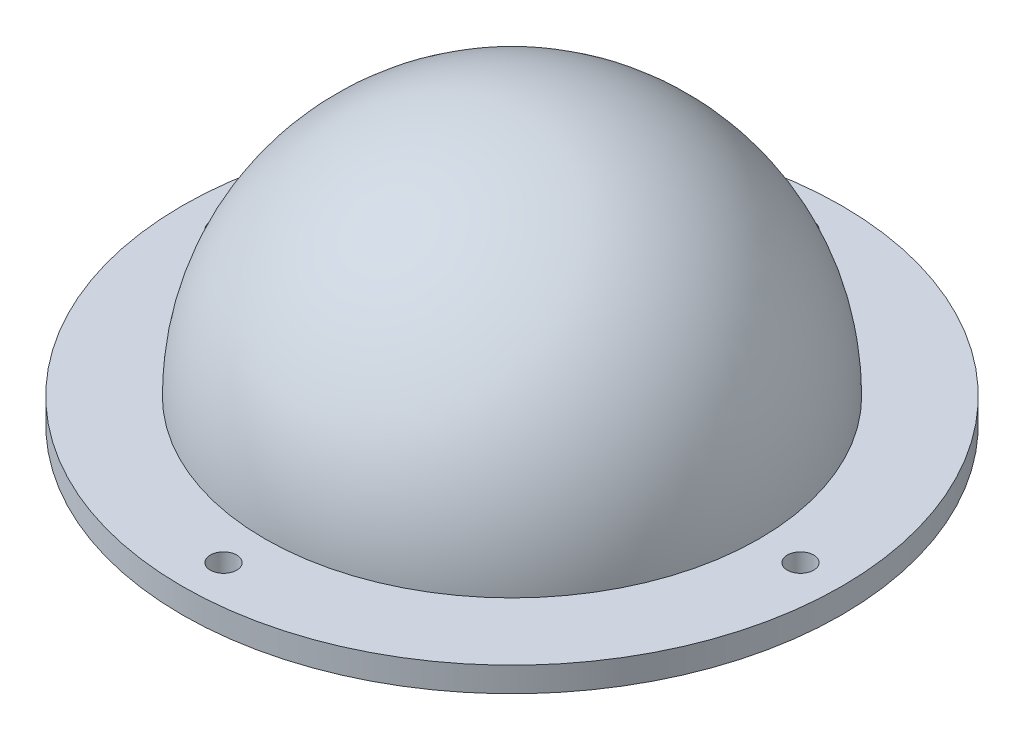
SolidWorks part; units mm, degrees
ref_plane "前视基准面" through (0, 0, 0) normal (0, 0, 1) x (1, 0, 0)
ref_plane "上视基准面" through (0, 0, 0) normal (0, 1, 0) x (1, 0, 0)
ref_plane "右视基准面" through (0, 0, 0) normal (1, 0, 0) x (0, 0, -1)
sketch "草图1" plane through (0, 0, 0) normal (0, 0, 1) x (1, 0, 0)
  line L0 (-30, 0) -> (-29, 0)
  line L2 (0, 30) -> (0, 29)
  line L3 (0, 29) -> (0, 0) construction
  arc A0 (0, 30) -> (-30, 0) centre (0, 0) ccw
  arc A1 (0, 29) -> (-29, 0) centre (0, 0) ccw
  dimension "D1" = 60
  dimension "D2" = 58
  dimension "D3" = 29
revolve "旋转1" add sketch "草图1" angle 360 about L3
sketch "草图2" plane through (0, 0, 0) normal (0, -1, 0) x (1, 0, 0)
  circle A0 centre (0, 0) radius 40
  circle A1 centre (0, 0) radius 28.5
  circle A2 centre (0, 0) radius 35 construction
  circle A3 centre (0, 35) radius 1.6
  circle A4 centre (35, 0) radius 1.6
  circle A5 centre (0, -35) radius 1.6
  circle A6 centre (-35, 0) radius 1.6
  point P16 (0, 0)
  dimension "D1" = 57
  dimension "D2" = 80
  dimension "D3" = 70
  dimension "D4" = 3.2
  dimension "D6" = 35
  dimension "D7" = 70
  dimension "D5" = 4
extrude "凸台-拉伸1" add sketch "草图2" along normal blind 3 separate body
sketch "草图3" plane through (0, -3, 0) normal (0, -1, 0) x (1, 0, 0)
  circle A0 centre (0, 0) radius 29
  dimension "D1" = 58
extrude "切除-拉伸1" cut sketch "草图3" against normal blind 3
